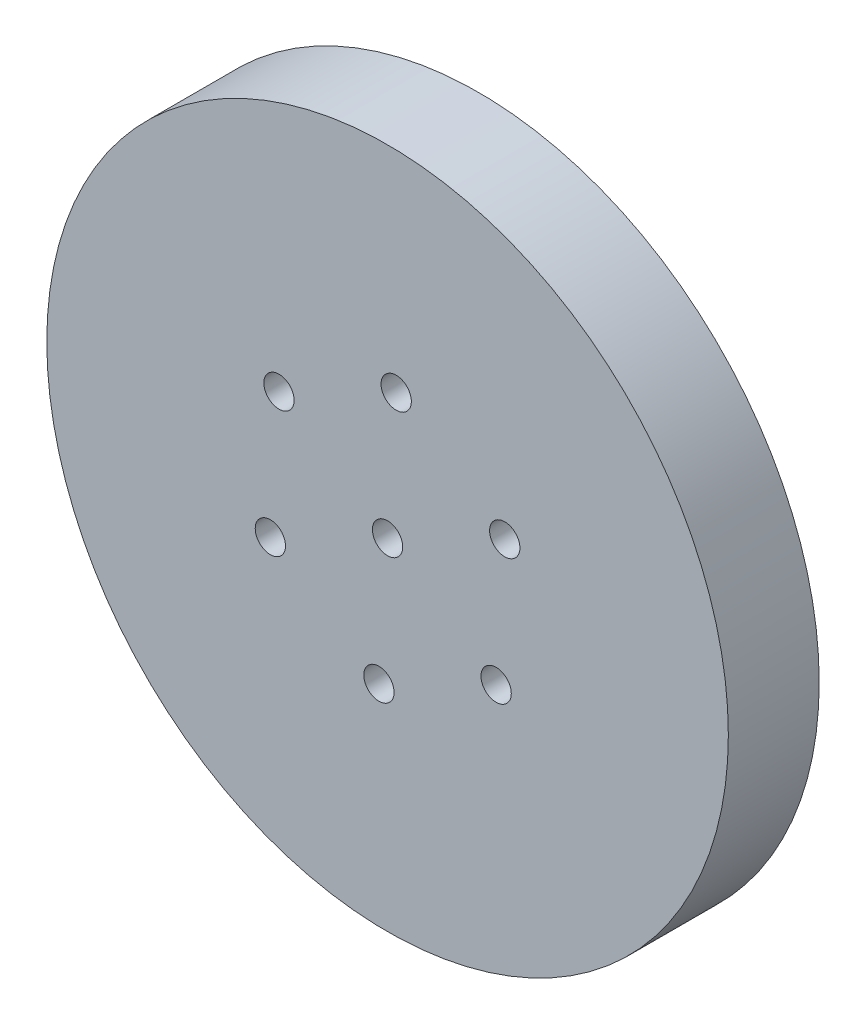
SolidWorks part; units mm, degrees
ref_plane "前视基准面" through (0, 0, 0) normal (0, 0, 1) x (1, 0, 0)
ref_plane "上视基准面" through (0, 0, 0) normal (0, 1, 0) x (1, 0, 0)
ref_plane "右视基准面" through (0, 0, 0) normal (1, 0, 0) x (0, 0, -1)
sketch "草图1" plane through (0, 0, 0) normal (0, 0, 1) x (1, 0, 0)
  circle A0 centre (0, 0) radius 45
extrude "凸台-拉伸1" add sketch "草图1" along normal blind 12
sketch "草图5" plane through (0, 0, 0) normal (0, 0, -1) x (-1, 0, 0)
  circle A0 centre (-15.4763, 7.6189) radius 2
  circle A1 centre (-1.1399, 17.2123) radius 2
  circle A2 centre (14.3363, 9.5934) radius 2
  circle A3 centre (15.4763, -7.6189) radius 2
  circle A4 centre (1.1399, -17.2123) radius 2
  circle A5 centre (-14.3363, -9.5934) radius 2
  point P15 (0, 0)
  dimension "D1" = 17.25
  dimension "D2" = 6
extrude "切除-拉伸1" cut sketch "草图5" against normal blind 20
sketch "草图6" plane through (0, 0, 0) normal (0, 0, -1) x (-1, 0, 0)
  circle A0 centre (0, 0) radius 2
extrude "切除-拉伸2" cut sketch "草图6" against normal blind 21
